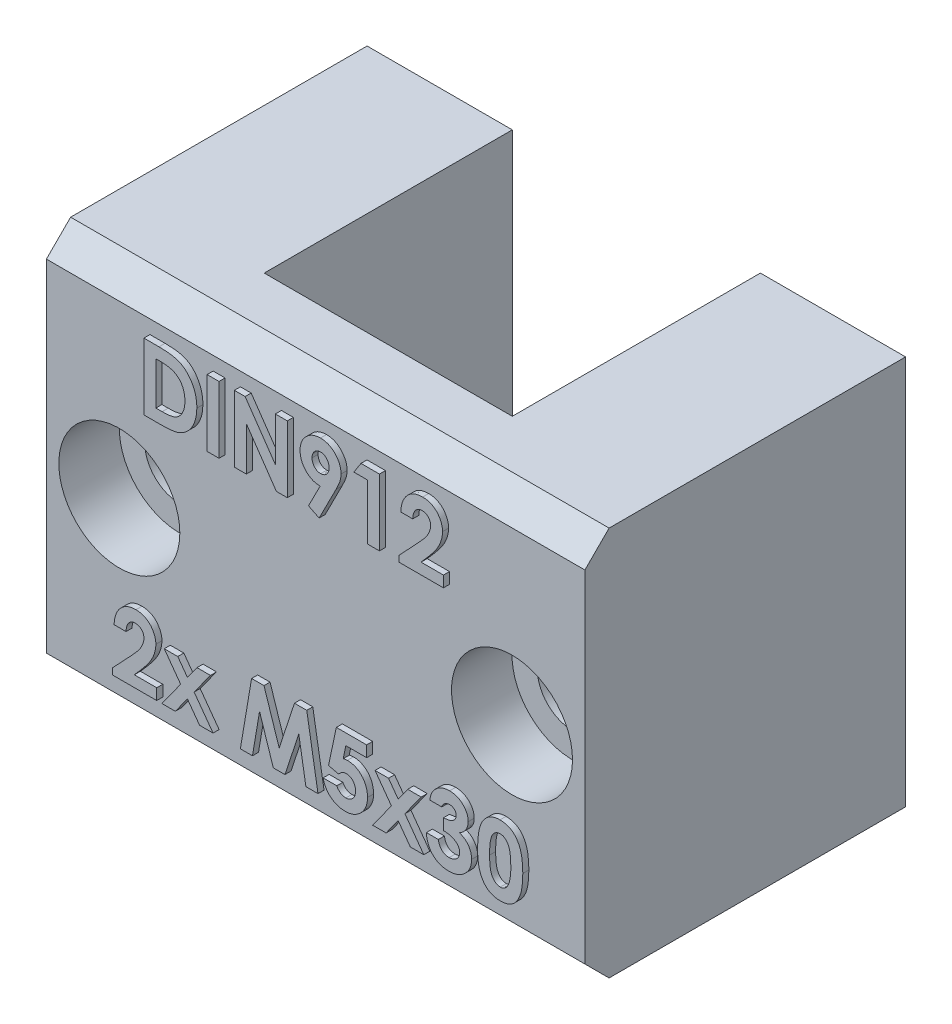
SolidWorks part; units mm, degrees
material "PETG"
ref_plane "Płaszczyzna przednia" through (0, 0, 0) normal (0, 0, 1) x (1, 0, 0)
ref_plane "Płaszczyzna górna" through (0, 0, 0) normal (0, 1, 0) x (1, 0, 0)
ref_plane "Płaszczyzna prawa" through (0, 0, 0) normal (1, 0, 0) x (0, 0, -1)
sketch "Sketch1" plane through (0, 0, 0) normal (0, 0, 1) x (1, 0, 0)
  line L1 (0, 0) -> (44.5, 0)
  line L2 (0, 0) -> (0, 32.2)
  line L3 (0, 32.2) -> (44.5, 32.2)
  line L4 (44.5, 0) -> (44.5, 32.2)
  dimension "D1" = 44.5
  dimension "D2" = 32.2
extrude "Boss-Extrude1" add sketch "Sketch1" along normal blind 6
sketch "Sketch2" plane through (0, 0, 0) normal (0, 0, -1) x (-1, 0, 0)
  line L0 (0, 0) -> (-44.5, 0) construction
  line L1 (-44.5, 32.2) -> (-32.5, 32.2)
  line L2 (-44.5, 32.2) -> (-44.5, 0)
  line L3 (-44.5, 0) -> (-32.5, 0)
  line L4 (-32.5, 32.2) -> (-32.5, 0)
  line L5 (-44.5, 32.2) -> (0, 32.2) construction
  line L6 (0, 0) -> (-12, 0)
  line L7 (0, 0) -> (0, 32.2)
  line L8 (0, 32.2) -> (-12, 32.2)
  line L9 (-12, 0) -> (-12, 32.2)
  dimension "D1" = 12
extrude "Boss-Extrude2" add sketch "Sketch2" along normal blind 20.5
hole_wizard "CBORE for M5 Hex Socket Head Cap Screw1" positions "Sketch3" profile "Sketch4" counterbore size "M5" standard "DIN" end condition through all
sketch "Sketch3" plane through (0, 0, 6) normal (0, 0, 1) x (1, 0, 0)
  point P0 (6.025, 16.1)
  point P2 (38.475, 16.1)
sketch "Sketch4" plane through (6.025, 16.1, 6) normal (1, 0, 0) x (0, -1, 0)
  line L0 (0, 0) -> (0, 26.5)
  line L1 (0, 26.5) -> (2.9, 26.5)
  line L3 (2.9, 26.5) -> (2.9, 5)
  line L4 (2.9, 5) -> (5, 5)
  line L5 (5, 5) -> (5, 0)
  line L7 (5, 0) -> (0, 0)
  line L11 (0, -6.35) -> (0, 107.95) construction
  dimension "Thru Hole Dia." = 5.8
  dimension "Thru Hole Depth" = 26.5
  dimension "C'Bore Dia." = 10
  dimension "C'Bore Depth" = 5
sketch "Sketch6" plane through (0, 0, 0) normal (0, 0, -1) x (-1, 0, 0)
  line L0 (-31.5, 1) -> (-13, 1)
  line L1 (-13, 1) -> (-13, 31.2)
  line L2 (-13, 31.2) -> (-31.5, 31.2)
  line L3 (-31.5, 31.2) -> (-31.5, 1)
  line L4 (-32.5, 0) -> (-12, 0)
  line L5 (-12, 0) -> (-12, 32.2)
  line L6 (-12, 32.2) -> (-32.5, 32.2)
  line L7 (-32.5, 32.2) -> (-32.5, 0)
  line L8 (-32.5, 0) -> (-12, 0)
  line L9 (-12, 0) -> (-12, 32.2)
  line L10 (-12, 32.2) -> (-32.5, 32.2)
  line L11 (-32.5, 32.2) -> (-32.5, 0)
  dimension "D1" = 0
  dimension "D2" = 1
extrude "Cut-Extrude1" cut sketch "Sketch6" against normal blind 1 contours L2 L3 L0 L1
chamfer "Chamfer1" distance 2 angle 45 2 edges at (22.25, 0, 6) (22.25, 32.2, 6)
sketch "Sketch7" plane through (0, 0, 6) normal (0, 0, 1) x (1, 0, 0)
  text T0 " DIN912\r\n\r\n2x M5x30" font "Century Gothic" height 5.5
extrude "Boss-Extrude3" add sketch "Sketch7" along normal blind 0.5
